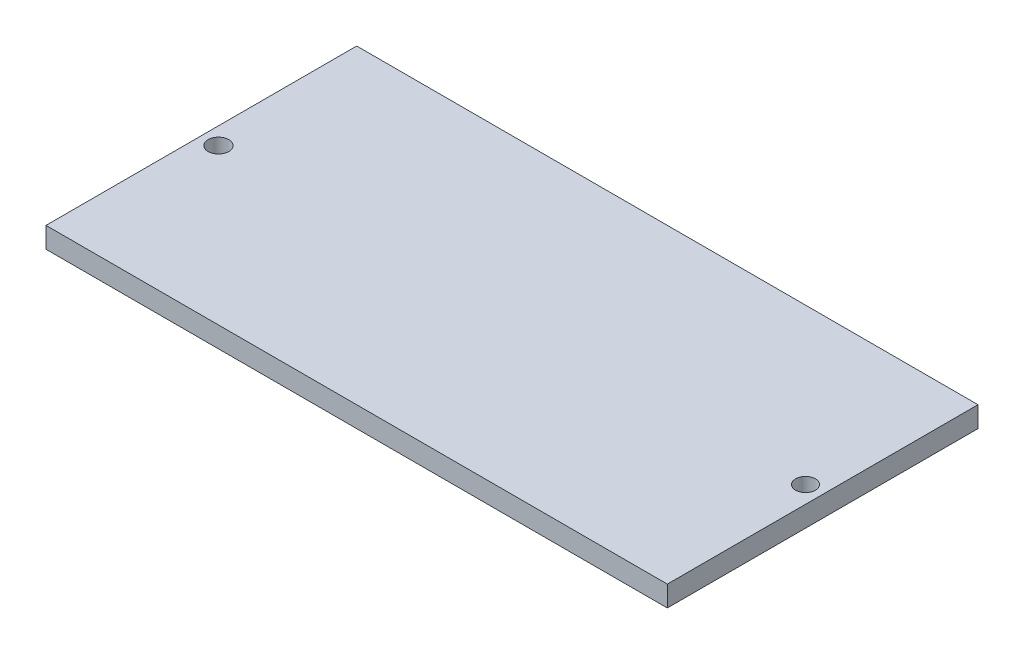
SolidWorks part; units mm, degrees
ref_plane "Front Plane" through (0, 0, 0) normal (0, 0, 1) x (1, 0, 0)
ref_plane "Top Plane" through (0, 0, 0) normal (0, 1, 0) x (1, 0, 0)
ref_plane "Right Plane" through (0, 0, 0) normal (1, 0, 0) x (0, 0, -1)
sketch "Sketch1" plane through (0, 0, 0) normal (0, 1, 0) x (1, 0, 0)
  line L1 (30.0073, -15.0055) -> (-30.0073, -15.0055)
  line L2 (30.0073, -15.0055) -> (30.0073, 15.0055)
  line L3 (30.0073, 15.0055) -> (-30.0073, 15.0055)
  line L4 (-30.0073, -15.0055) -> (-30.0073, 15.0055)
  line L5 (30.0073, -15.0055) -> (-30.0073, 15.0055) construction
  line L6 (30.0073, 15.0055) -> (-30.0073, -15.0055) construction
  point P0 (0, 0)
extrude "Boss-Extrude3" add sketch "Sketch1" along normal blind 2
sketch "Sketch5" plane through (0, 2, 0) normal (0, 1, 0) x (1, 0, 0)
  line L0 (-30.0073, 0) -> (-28.3555, 0) construction
  line L1 (-30.0073, 15.0055) -> (-30.0073, -15.0055) construction
  line L2 (30.0073, 0) -> (28.3555, 0) construction
  line L3 (30.0073, -15.0055) -> (30.0073, 15.0055) construction
  circle A0 centre (28.3555, 0) radius 0.9581
  circle A1 centre (-28.3555, 0) radius 1
extrude "Cut-Extrude2" cut sketch "Sketch5" against normal blind 2
sketch "Sketch7" plane through (0, 0, 0) normal (0, 0, 1) x (1, 0, 0)
  line L0 (-30.0073, 2) -> (0, 2) construction
  line L1 (-30.0073, 2) -> (-30.0073, 0) construction
  line L2 (-30.0073, 2) -> (30.0073, 2) construction
  line L3 (30.0073, 2) -> (0, 2) construction
  line L9 (0, -3.5846) -> (0, 3.5846) construction
  line L10 (7.4988, 0) -> (8.9619, 0)
  line L16 (8.9619, 0) -> (8.9619, -3.1761)
  line L17 (21.0454, -3.1761) -> (8.9619, -3.1761)
  line L19 (-30.0073, 1) -> (30.0073, 1) construction
  line L20 (30.0073, 2) -> (30.0073, 0) construction
  line L21 (-7.4988, 0) -> (-7.4988, -4.5174)
  line L22 (-22.5086, -4.5174) -> (-7.4988, -4.5174)
  line L23 (-22.5086, 0) -> (-22.5086, -4.5174)
  line L24 (-22.5086, 0) -> (-21.0454, 0)
  line L25 (-21.0454, 0) -> (-21.0454, -3.1761)
  line L26 (-21.0454, -3.1761) -> (-8.9619, -3.1761)
  line L27 (-8.9619, 0) -> (-8.9619, -3.1761)
  line L28 (-7.4988, 0) -> (-8.9619, 0)
  line L29 (21.0454, 0) -> (21.0454, -3.1761)
  line L30 (22.5086, 0) -> (21.0454, 0)
  line L31 (22.5086, 0) -> (22.5086, -4.5174)
  line L32 (22.5086, -4.5174) -> (7.4988, -4.5174)
  line L33 (7.4988, 0) -> (7.4988, -4.5174)
  point P9 (-15.0037, 2)
  point P15 (-15.0037, 2)
extrude "Boss-Extrude5" add sketch "Sketch7" along normal blind 10 and the other way blind 10
